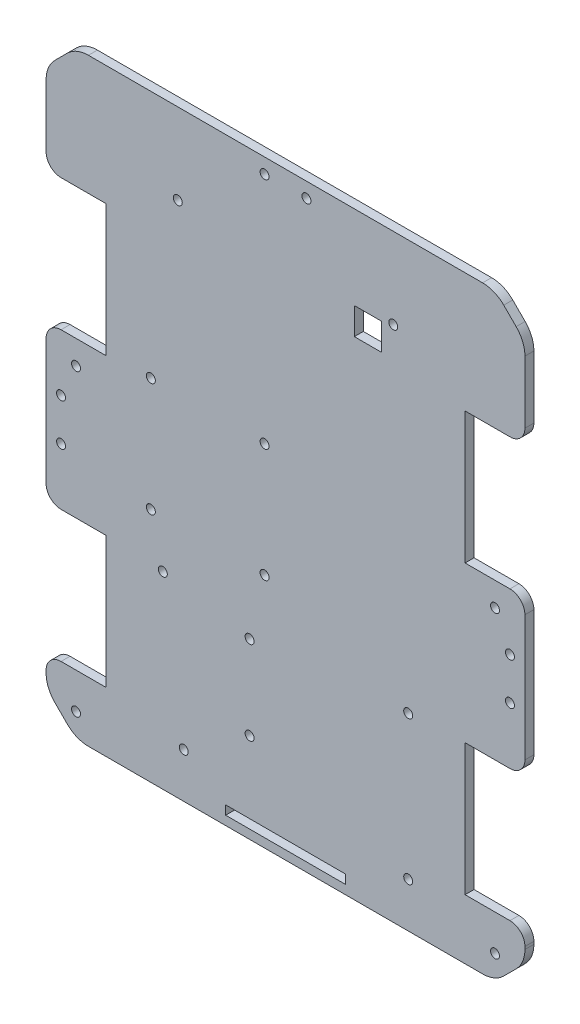
SolidWorks part; units mm, degrees
ref_plane "Front Plane" through (0, 0, 0) normal (0, 0, 1) x (1, 0, 0)
ref_plane "Top Plane" through (0, 0, 0) normal (0, 1, 0) x (1, 0, 0)
ref_plane "Right Plane" through (0, 0, 0) normal (1, 0, 0) x (0, 0, -1)
sketch "Sketch2" plane through (0, 0, 0) normal (0, 0, 1) x (1, 0, 0)
  line L0 (0, 0) -> (0, 209.7561) construction
  line L1 (-80, 167.8049) -> (-80, 137.8049)
  line L2 (-80, 137.8049) -> (-60, 137.8049)
  line L3 (-60, 137.8049) -> (-60, 93.8049)
  line L4 (-60, 93.8049) -> (-80, 93.8049)
  line L5 (-80, 93.8049) -> (-80, 41.8049)
  line L6 (-80, 41.8049) -> (-60, 41.8049)
  line L7 (-60, 41.8049) -> (-60, -2.1951)
  line L8 (-60, -2.1951) -> (-80, -2.1951)
  line L9 (-80, -2.1951) -> (-80, -12.1951)
  line L10 (-80, -12.1951) -> (-70, -22.1951)
  line L11 (-70, -22.1951) -> (70, -22.1951)
  line L12 (-80, 167.8049) -> (-70, 177.8049)
  line L13 (-70, 177.8049) -> (70, 177.8049)
  line L14 (0, 177.8049) -> (0, 209.7561) construction
  line L15 (0, 0) -> (0, -22.1951) construction
  line L16 (80, 167.8049) -> (70, 177.8049)
  line L17 (80, -12.1951) -> (70, -22.1951)
  line L18 (80, -2.1951) -> (80, -12.1951)
  line L19 (60, -2.1951) -> (80, -2.1951)
  line L20 (60, 41.8049) -> (60, -2.1951)
  line L21 (80, 41.8049) -> (60, 41.8049)
  line L22 (80, 93.8049) -> (80, 41.8049)
  line L23 (60, 93.8049) -> (80, 93.8049)
  line L24 (60, 137.8049) -> (60, 93.8049)
  line L25 (80, 137.8049) -> (60, 137.8049)
  line L26 (80, 167.8049) -> (80, 137.8049)
  point P17 (0, 0)
  point P18 (0, 0)
  point P19 (0, 0)
  dimension "D1" = 52
  dimension "D2" = 135
  dimension "D3" = 135
  dimension "D4" = 44
  dimension "D5" = 44
  dimension "D6" = 20
  dimension "D7" = 10
  dimension "D8" = 10
  dimension "D9" = 10
  dimension "D10" = 30
  dimension "D11" = 80
  dimension "D12" = 120
extrude "Boss-Extrude2" add sketch "Sketch2" along normal blind 3
sketch "Sketch3" plane through (0, 0, 3) normal (0, 0, 1) x (1, 0, 0)
  line L0 (-60, 93.8049) -> (-80, 93.8049) construction
  line L1 (-80, 93.8049) -> (-80, 41.8049) construction
  line L2 (80, 41.8049) -> (80, 93.8049) construction
  line L3 (60, -2.1951) -> (60, 41.8049) construction
  line L4 (70, 177.8049) -> (-70, 177.8049) construction
  line L5 (-70, -22.1951) -> (70, -22.1951) construction
  line L6 (-20, -16.1951) -> (20, -16.1951)
  line L7 (-80, 41.8049) -> (-60, 41.8049) construction
  line L8 (-20, -16.1951) -> (-20, -19.1951)
  line L9 (-20, -19.1951) -> (20, -19.1951)
  line L10 (20, -16.1951) -> (20, -19.1951)
  line L14 (23, 149.8049) -> (32, 149.8049)
  line L15 (23, 149.8049) -> (23, 140.8049)
  line L16 (23, 140.8049) -> (32, 140.8049)
  line L17 (32, 149.8049) -> (32, 140.8049)
  circle A0 centre (-75, 74.8049) radius 1.5
  circle A1 centre (-75, 60.8049) radius 1.5
  circle A2 centre (75, 74.8049) radius 1.5
  circle A3 centre (75, 60.8049) radius 1.5
  circle A4 centre (-34, -7.1951) radius 1.5
  circle A5 centre (41, -7.1951) radius 1.5
  circle A6 centre (41, 40.8049) radius 1.5
  circle A7 centre (-41, 40.8049) radius 1.5
  circle A8 centre (-12, 35.8049) radius 1.5
  circle A9 centre (-12, 7.8049) radius 1.5
  circle A10 centre (-45, 94.8049) radius 1.5
  circle A11 centre (-7, 94.8049) radius 1.5
  circle A12 centre (-7, 56.8049) radius 1.5
  circle A13 centre (-45, 56.8049) radius 1.5
  circle A14 centre (-36, 150.8049) radius 1.5
  circle A15 centre (36, 150.8049) radius 1.5
  circle A16 centre (-7, 172.8049) radius 1.5
  circle A17 centre (7, 172.8049) radius 1.5
  point P60 (0, 0)
  dimension "D2" = 3
  dimension "D14" = 3
  dimension "D19" = 3
  dimension "D31" = 3
  dimension "D35" = 3
  dimension "D1" = 14
  dimension "D3" = 19
  dimension "D4" = 5
  dimension "D5" = 5
  dimension "D6" = 82
  dimension "D7" = 48
  dimension "D8" = 75
  dimension "D9" = 28
  dimension "D10" = 53
  dimension "D11" = 15
  dimension "D12" = 19
  dimension "D13" = 15
  dimension "D15" = 38
  dimension "D16" = 38
  dimension "D17" = 15
  dimension "D18" = 35
  dimension "D20" = 3
  dimension "D21" = 40
  dimension "D22" = 50
  dimension "D23" = 3
  dimension "D24" = 72
  dimension "D25" = 27
  dimension "D26" = 34
  dimension "D27" = 9
  dimension "D28" = 9
  dimension "D29" = 28
  dimension "D30" = 4
  dimension "D32" = 14
  dimension "D33" = 5
  dimension "D34" = 63
extrude "Cut-Extrude1" cut sketch "Sketch3" against normal through all
fillet "Fillet1" radius 10 8 edges at (80, 167.8049, 1.5) (-80, 167.8049, 1.5) (-70, 177.8049, 1.5) (70, 177.8049, 1.5) (80, -12.1951, 1.5) (70, -22.1951, 1.5) (-80, -12.1951, 1.5) (-70, -22.1951, 1.5)
sketch "Sketch4" plane through (0, 0, 3) normal (0, 0, 1) x (1, 0, 0)
  line L0 (-65.8579, -22.1951) -> (65.8579, -22.1951) construction
  line L1 (-80, -2.1951) -> (-80, -8.053) construction
  line L2 (80, -8.053) -> (80, -2.1951) construction
  line L3 (80, 93.8049) -> (60, 93.8049) construction
  circle A0 centre (-70, 85.8049) radius 1.5
  circle A1 centre (70, 85.8049) radius 1.5
  circle A2 centre (-70, -14.1951) radius 1.5
  circle A3 centre (70, -14.1951) radius 1.5
  point P8 (0, 0)
  point P9 (0, 0)
  point P10 (0, 0)
  point P11 (0, 0)
  dimension "D5" = 3
  dimension "D1" = 8
  dimension "D2" = 10
  dimension "D3" = 10
  dimension "D4" = 8
extrude "Cut-Extrude2" cut sketch "Sketch4" against normal through all
fillet "Fillet2" radius 5 8 edges at (80, 93.8049, 1.5) (80, 41.8049, 1.5) (-80, 41.8049, 1.5) (-80, 93.8049, 1.5) (-80, -2.1951, 1.5) (80, -2.1951, 1.5) (80, 137.8049, 1.5) (-80, 137.8049, 1.5)
